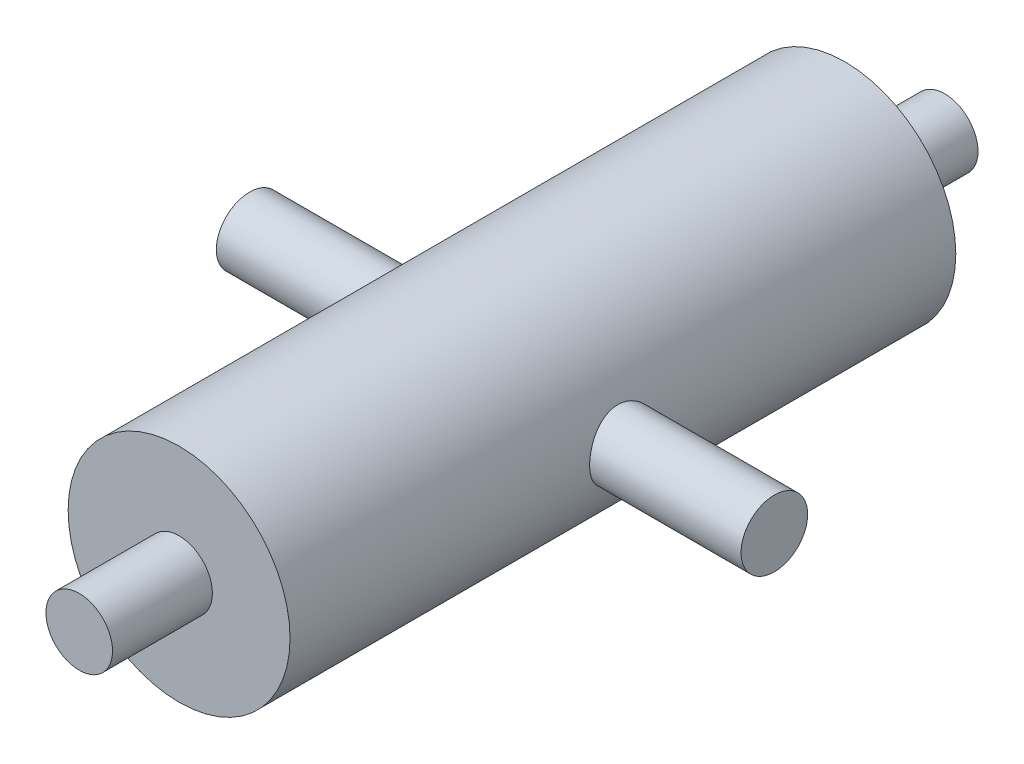
SolidWorks part; units mm, degrees
ref_plane "Front Plane" through (0, 0, 0) normal (0, 0, 1) x (1, 0, 0)
ref_plane "Top Plane" through (0, 0, 0) normal (0, 1, 0) x (1, 0, 0)
ref_plane "Right Plane" through (0, 0, 0) normal (1, 0, 0) x (0, 0, -1)
sketch "Sketch1" plane through (0, 0, 0) normal (0, 0, 1) x (1, 0, 0)
  circle A0 centre (0, 0) radius 10
  dimension "D1" = 20
extrude "Boss-Extrude1" add sketch "Sketch1" along normal blind 60
sketch "Sketch2" plane through (0, 0, 0) normal (1, 0, 0) x (0, 0, -1)
  line L0 (-60, 0) -> (0, 0) construction
  line L1 (-60, 10) -> (-60, -10) construction
  circle A0 centre (-30, 0) radius 3
  dimension "D1" = 6
extrude "Boss-Extrude2" add sketch "Sketch2" along normal mid plane 47.29
sketch "Sketch3" plane through (0, 0, 60) normal (0, 0, 1) x (1, 0, 0)
  circle A0 centre (0, 0) radius 3
  dimension "D1" = 6
extrude "Boss-Extrude3" add sketch "Sketch3" along normal blind 9 and the other way blind 69
